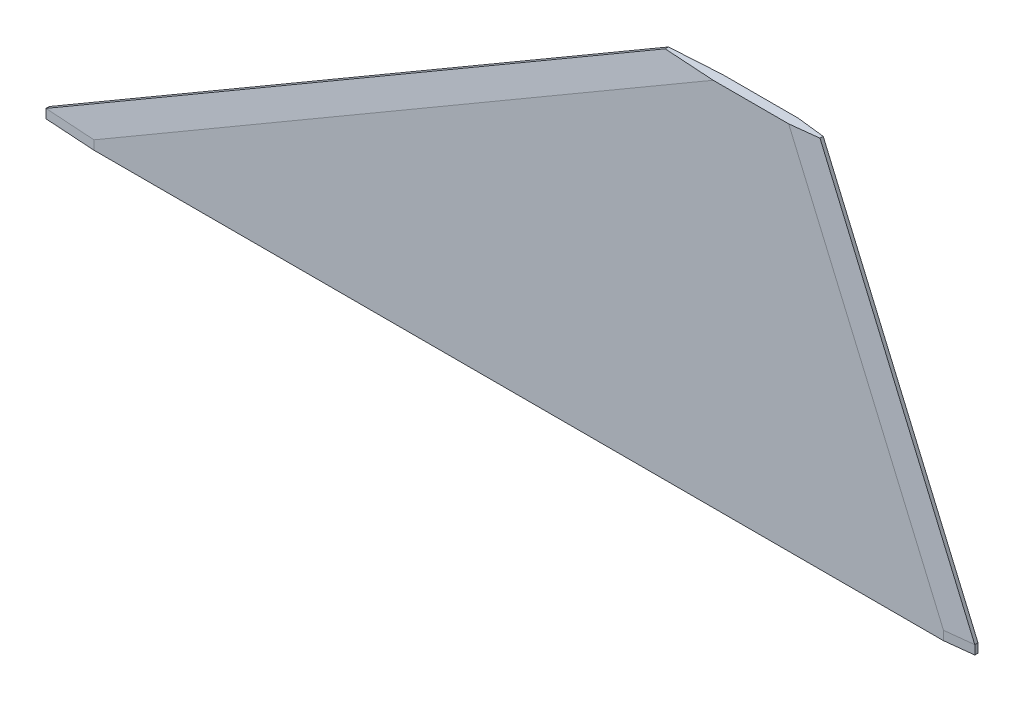
SolidWorks part; units mm, degrees
material "Hexcel AS4C (3000 Filaments)"
ref_plane "Front Plane" through (0, 0, 0) normal (0, 0, 1) x (1, 0, 0)
ref_plane "Top Plane" through (0, 0, 0) normal (0, 1, 0) x (1, 0, 0)
ref_plane "Right Plane" through (0, 0, 0) normal (1, 0, 0) x (0, 0, -1)
sketch "Sketch1" plane through (0, 0, 0) normal (0, 0, 1) x (1, 0, 0)
  line L0 (0, 0) -> (457.2, 0)
  line L1 (457.2, 0) -> (381, 177.8)
  line L2 (381, 177.8) -> (304.8, 177.8)
  line L3 (304.8, 177.8) -> (0, 0)
  dimension "D1" = 457.2
  dimension "D2" = 76.2
  dimension "D3" = 304.8
  dimension "D4" = 177.8
extrude "Boss-Extrude1" add sketch "Sketch1" along normal blind 4.7625
chamfer "Chamfer1" distance 1.5875 distance2 12.7 2 edges at (152.4, 88.9, 0) (152.4, 88.9, 4.7625)
chamfer "Chamfer2" distance 1.5875 distance2 12.7 2 edges at (419.1, 88.9, 0) (419.1, 88.9, 4.7625)
sketch "Sketch2" plane through (0, 0, 0) normal (0, -1, 0) x (1, 0, 0)
  line L8 (25.2049, 0) -> (443.3828, 0)
  line L9 (443.3828, 0) -> (457.2, 1.5875)
  line L10 (457.2, 1.5875) -> (457.2, 3.175)
  line L11 (457.2, 3.175) -> (443.3828, 4.7625)
  line L12 (443.3828, 4.7625) -> (25.2049, 4.7625)
  line L13 (25.2049, 4.7625) -> (0, 3.175)
  line L14 (0, 3.175) -> (0, 1.5875)
  line L15 (0, 1.5875) -> (25.2049, 0)
  line L16 (25.2049, 0) -> (443.3828, 0)
  line L17 (443.3828, 0) -> (457.2, 1.5875)
  line L18 (457.2, 1.5875) -> (457.2, 3.175)
  line L19 (457.2, 3.175) -> (443.3828, 4.7625)
  line L20 (443.3828, 4.7625) -> (25.2049, 4.7625)
  line L21 (25.2049, 4.7625) -> (0, 3.175)
  line L22 (0, 3.175) -> (0, 1.5875)
  line L23 (0, 1.5875) -> (25.2049, 0)
  dimension "D1" = 0
extrude "Boss-Extrude2" add sketch "Sketch2" along normal blind 4.445
sketch "Base Centerline" plane through (0, -4.445, 0) normal (0, -1, 0) x (1, 0, 0)
  line L0 (0, 2.3812) -> (457.2, 2.3812) construction
  line L1 (0, 3.175) -> (0, 1.5875) construction
  line L2 (457.2, 1.5875) -> (457.2, 3.175) construction
sketch "Sketch3" plane through (0, 0, 4.7625) normal (0, 0, 1) x (1, 0, 0)
  line L0 (144.78, 84.455) -> (169.9849, 84.455) construction
  line L1 (0, 0) -> (304.8, 177.8) construction
  line L2 (381, 177.8) -> (457.2, 0) construction
  line L3 (443.3828, 0) -> (367.1828, 177.8) construction
  line L4 (330.0049, 177.8) -> (25.2049, 0) construction
  line L5 (443.3828, 0) -> (367.1828, 177.8)
  line L6 (330.0049, 177.8) -> (25.2049, 0)
  line L7 (0, -4.445) -> (457.2, -4.445) construction
  line L8 (407.1878, 84.455) -> (421.005, 84.455) construction
  dimension "D1" = 88.9
